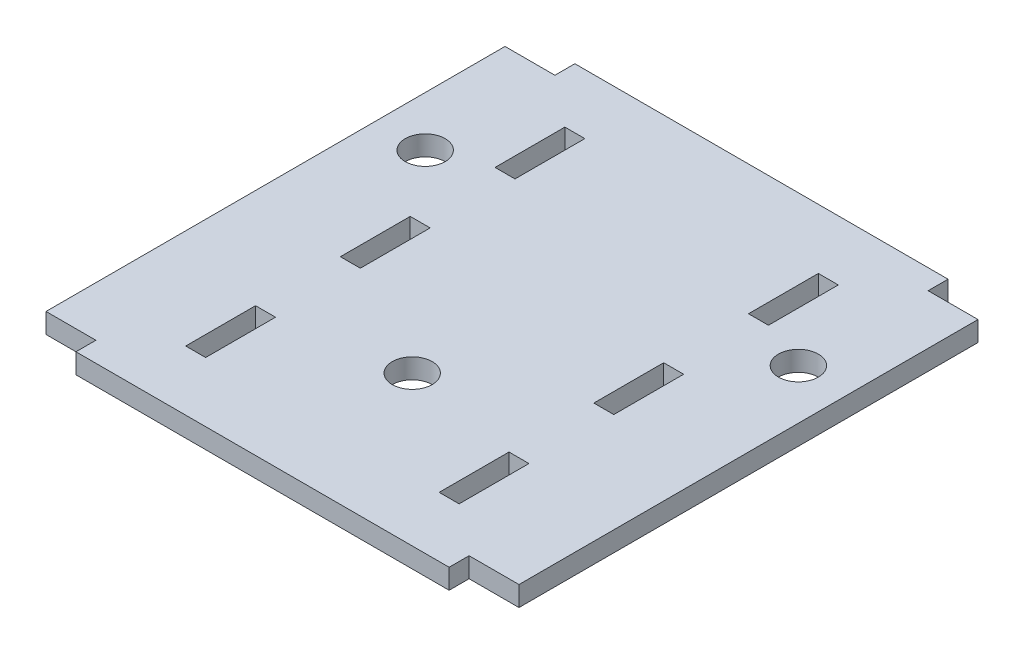
SolidWorks part; units mm, degrees
ref_plane "Front Plane" through (0, 0, 0) normal (0, 0, 1) x (1, 0, 0)
ref_plane "Top Plane" through (0, 0, 0) normal (0, 1, 0) x (1, 0, 0)
ref_plane "Right Plane" through (0, 0, 0) normal (1, 0, 0) x (0, 0, -1)
sketch "Sketch1" plane through (0, 0, 0) normal (0, 1, 0) x (1, 0, 0)
  line L0 (-30.9995, -41.9807) -> (-32.9995, -41.9807)
  line L1 (-70.7995, 2.0193) -> (32.2005, 2.0193)
  line L2 (-70.7995, 2.0193) -> (-70.7995, -47.9807)
  line L3 (-70.7995, -47.9807) -> (32.2005, -47.9807)
  line L4 (32.2005, 2.0193) -> (32.2005, -47.9807)
  line L5 (-30.9995, -41.9807) -> (-30.9995, -34.9807)
  line L6 (-30.9995, -34.9807) -> (-32.9995, -34.9807)
  line L7 (-32.9995, -41.9807) -> (-32.9995, -34.9807)
  line L8 (-30.9995, -26.4807) -> (-32.9995, -26.4807)
  line L9 (-30.9995, -26.4807) -> (-30.9995, -19.4807)
  line L10 (-30.9995, -19.4807) -> (-32.9995, -19.4807)
  line L11 (-32.9995, -26.4807) -> (-32.9995, -19.4807)
  line L12 (-30.9995, -10.9807) -> (-32.9995, -10.9807)
  line L13 (-30.9995, -10.9807) -> (-30.9995, -3.9807)
  line L14 (-30.9995, -3.9807) -> (-32.9995, -3.9807)
  line L15 (-32.9995, -10.9807) -> (-32.9995, -3.9807)
  line L16 (-5.5995, -10.9807) -> (-7.5995, -10.9807)
  line L17 (-5.5995, -10.9807) -> (-5.5995, -3.9807)
  line L18 (-5.5995, -3.9807) -> (-7.5995, -3.9807)
  line L19 (-7.5995, -10.9807) -> (-7.5995, -3.9807)
  line L20 (-5.5995, -26.4807) -> (-7.5995, -26.4807)
  line L21 (-5.5995, -26.4807) -> (-5.5995, -19.4807)
  line L22 (-5.5995, -19.4807) -> (-7.5995, -19.4807)
  line L23 (-7.5995, -26.4807) -> (-7.5995, -19.4807)
  line L24 (-5.5995, -41.9807) -> (-7.5995, -41.9807)
  line L25 (-5.5995, -41.9807) -> (-5.5995, -34.9807)
  line L26 (-5.5995, -34.9807) -> (-7.5995, -34.9807)
  line L27 (-7.5995, -41.9807) -> (-7.5995, -34.9807)
  line L29 (-42.9995, -47.9807) -> (-37.9995, -47.9807)
  line L30 (-42.9995, -47.9807) -> (-42.9995, -45.9807)
  line L31 (-42.9995, -45.9807) -> (-37.9995, -45.9807)
  line L32 (-37.9995, -47.9807) -> (-37.9995, -45.9807)
  line L33 (-0.5995, -47.9807) -> (4.4005, -47.9807)
  line L34 (-0.5995, -47.9807) -> (-0.5995, -45.9807)
  line L35 (-0.5995, -45.9807) -> (4.4005, -45.9807)
  line L36 (4.4005, -47.9807) -> (4.4005, -45.9807)
  line L37 (-42.9995, 2.0193) -> (-37.9995, 2.0193)
  line L38 (-42.9995, 2.0193) -> (-42.9995, 0.0193)
  line L39 (-42.9995, 0.0193) -> (-37.9995, 0.0193)
  line L40 (-37.9995, 2.0193) -> (-37.9995, 0.0193)
  line L41 (-0.5995, 2.0193) -> (4.4005, 2.0193)
  line L42 (-0.5995, 2.0193) -> (-0.5995, 0.0193)
  line L43 (-0.5995, 0.0193) -> (4.4005, 0.0193)
  line L44 (4.4005, 2.0193) -> (4.4005, 0.0193)
  circle A0 centre (-37.9995, -12.9807) radius 2
  circle A1 centre (-0.5995, -12.9807) radius 2
  circle A2 centre (-19.2995, -32.9807) radius 2
  dimension "D21" = 4
  dimension "D22" = 4
  dimension "D24" = 23.4
  dimension "D25" = 23.4
  dimension "D27" = 15
  dimension "D29" = 4
  dimension "D31" = 51.5
  dimension "D1" = 50
  dimension "D2" = 103
  dimension "D4" = 7
  dimension "D5" = 2
  dimension "D6" = 7
  dimension "D7" = 2
  dimension "D8" = 7
  dimension "D9" = 2
  dimension "D10" = 7
  dimension "D11" = 2
  dimension "D12" = 7
  dimension "D13" = 2
  dimension "D14" = 7
  dimension "D15" = 2
  dimension "D16" = 8.5
  dimension "D17" = 8.5
  dimension "D18" = 8.5
  dimension "D19" = 8.5
  dimension "D20" = 23.4
  dimension "D23" = 0
  dimension "D26" = 0
  dimension "D28" = 15
  dimension "D30" = 35
  dimension "D32" = 0
  dimension "D33" = 0
  dimension "D34" = 0
  dimension "D35" = 6
  dimension "D36" = 6
  dimension "D37" = 6
  dimension "D38" = 6
  dimension "D39" = 37.8
  dimension "D40" = 37.8
  dimension "D41" = 11.7
  dimension "D42" = 11.7
  dimension "D43" = 2
  dimension "D44" = 5
  dimension "D45" = 5
  dimension "D46" = 2
  dimension "D47" = 5
  dimension "D48" = 5
  dimension "D49" = 5
  dimension "D50" = 5
  dimension "D51" = 2
  dimension "D52" = 5
  dimension "D53" = 5
  dimension "D54" = 2
  dimension "D55" = 35
extrude "Boss-Extrude1" add sketch "Sketch1" along normal blind 2 contours L1 L44 L43 L42 L40 L39 L38 L2 L3 L30 L31 L32 L34 L35 L36 L4 A2 A1 A0 L0 L7 L6 L5 L8 L11 L10 L9 L12 L15 L14 L13 L16 L19 L18 L17 L20 L23 L22 L21
sketch "Sketch2" plane through (0, 0, 0) normal (0, -1, 0) x (-1, 0, 0)
  line L1 (70.7995, -47.9807) -> (42.9995, -47.9807)
  line L2 (70.7995, -47.9807) -> (70.7995, 2.0193)
  line L3 (70.7995, 2.0193) -> (42.9995, 2.0193)
  line L4 (42.9995, -47.9807) -> (42.9995, 2.0193)
  line L5 (-32.2005, -47.9807) -> (-4.4005, -47.9807)
  line L6 (-32.2005, -47.9807) -> (-32.2005, 2.0193)
  line L7 (-32.2005, 2.0193) -> (-4.4005, 2.0193)
  line L8 (-4.4005, -47.9807) -> (-4.4005, 2.0193)
extrude "Cut-Extrude1" cut sketch "Sketch2" against normal blind 10
